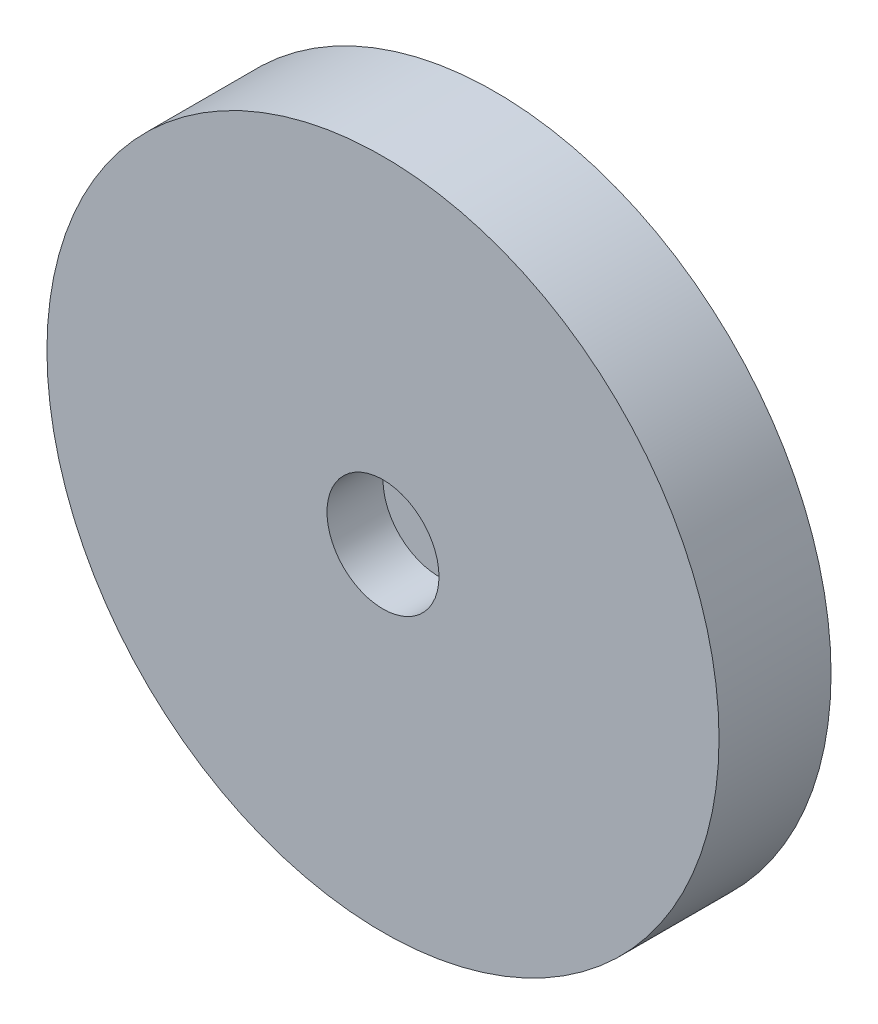
SolidWorks part; units mm, degrees
ref_plane "Front Plane" through (0, 0, 0) normal (0, 0, 1) x (1, 0, 0)
ref_plane "Top Plane" through (0, 0, 0) normal (0, 1, 0) x (1, 0, 0)
ref_plane "Right Plane" through (0, 0, 0) normal (1, 0, 0) x (0, 0, -1)
sketch "Sketch2" plane through (0, 0, 0) normal (0, 0, 1) x (1, 0, 0)
  circle A0 centre (0, 0) radius 150
  dimension "D1" = 300
extrude "Boss-Extrude1" add sketch "Sketch2" along normal blind 50
sketch "Sketch3" plane through (0, 0, 50) normal (0, 0, 1) x (1, 0, 0)
  circle A0 centre (0, 0) radius 25
  dimension "D1" = 50
extrude "Cut-Extrude1" cut sketch "Sketch3" against normal blind 25
